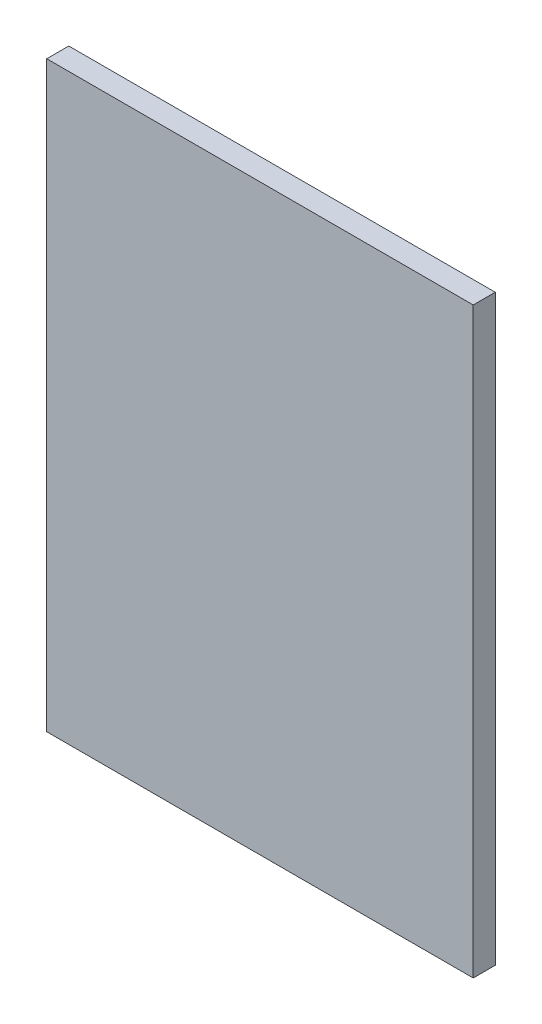
SolidWorks part; units mm, degrees
ref_plane "Plan de face" through (0, 0, 0) normal (0, 0, 1) x (1, 0, 0)
ref_plane "Plan de dessus" through (0, 0, 0) normal (0, 1, 0) x (1, 0, 0)
ref_plane "Plan de droite" through (0, 0, 0) normal (1, 0, 0) x (0, 0, -1)
sketch "Esquisse1" plane through (0, 0, 0) normal (0, 0, 1) x (1, 0, 0)
  line L1 (15, 20.5) -> (-15, 20.5)
  line L2 (15, 20.5) -> (15, -20.5)
  line L3 (15, -20.5) -> (-15, -20.5)
  line L4 (-15, 20.5) -> (-15, -20.5)
  line L5 (15, 20.5) -> (-15, -20.5) construction
  line L6 (15, -20.5) -> (-15, 20.5) construction
  point P0 (0, 0)
  dimension "D1" = 30
  dimension "D2" = 41
extrude "Boss.-Extru.1" add sketch "Esquisse1" along normal blind 1.55
